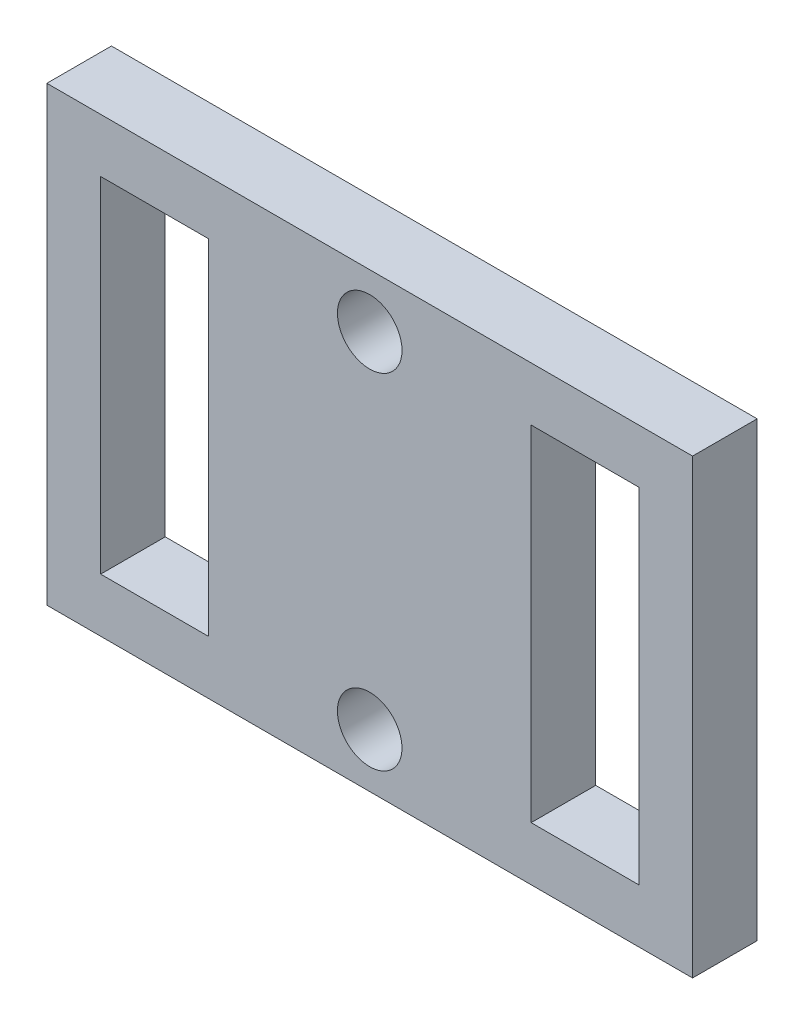
SolidWorks part; units mm, degrees
material "Thornel Mat VMA"
ref_plane "前视基准面" through (0, 0, 0) normal (0, 0, 1) x (1, 0, 0)
ref_plane "上视基准面" through (0, 0, 0) normal (0, 1, 0) x (1, 0, 0)
ref_plane "右视基准面" through (0, 0, 0) normal (1, 0, 0) x (0, 0, -1)
sketch "草图1" plane through (0, 0, 0) normal (0, 0, 1) x (1, 0, 0)
  line L0 (-15, 0) -> (15, 0) construction
  line L1 (-15, 10.5) -> (15, 10.5)
  line L2 (-15, 10.5) -> (-15, -10.5)
  line L3 (-15, -10.5) -> (15, -10.5)
  line L4 (15, 10.5) -> (15, -10.5)
  line L5 (-15, 10.5) -> (15, -10.5) construction
  line L6 (-15, -10.5) -> (15, 10.5) construction
  circle A0 centre (0, 8) radius 1.5
  circle A1 centre (0, -8) radius 1.5
  point P0 (0, 0)
  dimension "D3" = 8
  dimension "D4" = 3
  dimension "D1" = 21
  dimension "D2" = 30
extrude "凸台-拉伸1" add sketch "草图1" along normal blind 3
sketch "草图2" plane through (0, 0, 3) normal (0, 0, 1) x (1, 0, 0)
  line L0 (0, 10.5) -> (0, -10.5) construction
  line L1 (15, 10.5) -> (-15, 10.5) construction
  line L2 (-15, -10.5) -> (15, -10.5) construction
  line L3 (12.5, -8) -> (7.5, 8) construction
  line L4 (-12.5, 8) -> (-7.5, 8)
  line L5 (-12.5, 8) -> (-12.5, -8)
  line L6 (-12.5, -8) -> (-7.5, -8)
  line L7 (-7.5, 8) -> (-7.5, -8)
  line L8 (-12.5, 8) -> (-7.5, -8) construction
  line L9 (-12.5, -8) -> (-7.5, 8) construction
  line L10 (12.5, 8) -> (7.5, -8) construction
  line L11 (7.5, 8) -> (7.5, -8)
  line L12 (12.5, -8) -> (7.5, -8)
  line L13 (12.5, 8) -> (12.5, -8)
  line L14 (12.5, 8) -> (7.5, 8)
  point P6 (-10, 0)
  point P17 (10, 0)
  dimension "D1" = 16
  dimension "D2" = 5
  dimension "D3" = 7.5
extrude "切除-拉伸1" cut sketch "草图2" against normal through all
